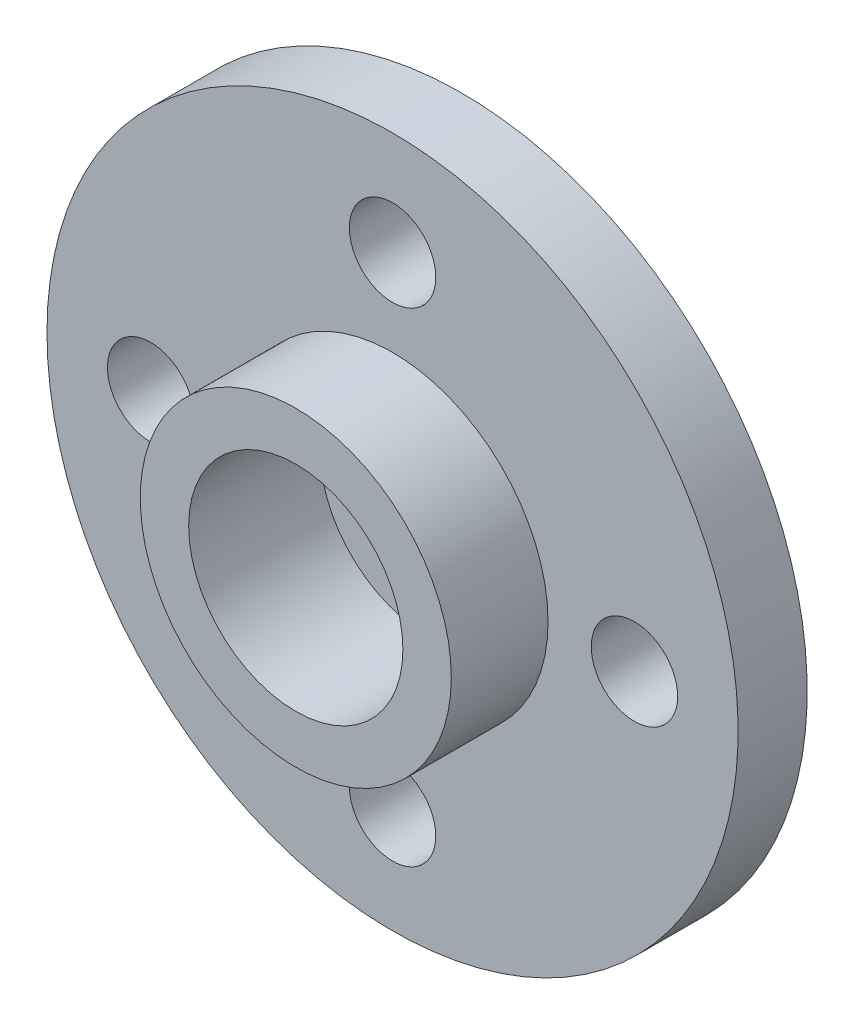
SolidWorks part; units mm, degrees
ref_plane "前视基准面" through (0, 0, 0) normal (0, 0, 1) x (1, 0, 0)
ref_plane "上视基准面" through (0, 0, 0) normal (0, 1, 0) x (1, 0, 0)
ref_plane "右视基准面" through (0, 0, 0) normal (1, 0, 0) x (0, 0, -1)
ref_plane "基准面4" through (0, -19.9, 0) normal (0, -1, 0) x (1, 0, 0)
sketch "草图1" plane through (0, -19.9, 0) normal (0, -1, 0) x (1, 0, 0)
  line L0 (-29.1026, -34.124) -> (-39.1026, -34.124)
  line L1 (-39.1026, -34.124) -> (-39.1026, -36.124)
  line L2 (-39.1026, -36.124) -> (-29.1026, -36.124)
  line L3 (-29.1026, -36.124) -> (-29.1026, -34.124)
  line L4 (-39.1026, -34.124) -> (-39.1026, -36.124) construction
revolve "旋转1" add sketch "草图1" angle 360 about L4
sketch "草图2" plane through (0, 0, -34.124) normal (0, 0, 1) x (1, 0, 0)
  circle A0 centre (-39.1026, -19.9) radius 4.5
extrude "凸台-拉伸1" add sketch "草图2" along normal blind 2.8
hole_wizard "Ø2.5 (2.5) 直径孔1" positions "草图4" profile "草图3" hole size "Ø2.5" standard "ANSI Metric"
sketch "草图4" plane through (0, 0, -34.124) normal (0, 0, 1) x (1, 0, 0)
  point P0 (-39.1026, -26.9)
  point P1 (-32.1026, -19.9)
  point P2 (-39.1026, -12.9)
  point P3 (-46.1026, -19.9)
sketch "草图3" plane through (-39.1026, -26.9, -34.124) normal (1, 0, 0) x (0, -1, 0)
  line L0 (0, 0) -> (0, 2)
  line L1 (0, 2) -> (1.25, 2)
  line L2 (1.25, 2) -> (1.25, 0)
  line L5 (1.25, 0) -> (0, 0)
  line L11 (0, -6.35) -> (0, 107.95) construction
  dimension "通孔孔直径" = 2.5
  dimension "通孔孔深度" = 2
hole_wizard "M3 六角头机械螺钉的柱形沉头孔1" positions "草图6" profile "草图5" counterbore size "M3" standard "ANSI Metric"
sketch "草图6" plane through (0, 0, -31.324) normal (0, 0, 1) x (1, 0, 0)
  point P0 (-39.1026, -19.9)
sketch "草图5" plane through (-39.1026, -19.9, -31.324) normal (1, 0, 0) x (0, -1, 0)
  line L0 (0, 0) -> (0, 4.8)
  line L1 (0, 4.8) -> (1.6, 4.8)
  line L3 (1.6, 4.8) -> (1.6, 3.8)
  line L4 (1.6, 3.8) -> (3.1, 3.8)
  line L5 (3.1, 3.8) -> (3.1, 0)
  line L7 (3.1, 0) -> (0, 0)
  line L11 (0, -6.35) -> (0, 107.95) construction
  dimension "通孔孔直径" = 3.2
  dimension "通孔孔深度" = 4.8
  dimension "柱形沉头孔直径" = 6.2
  dimension "柱形沉头孔深度" = 3.8
